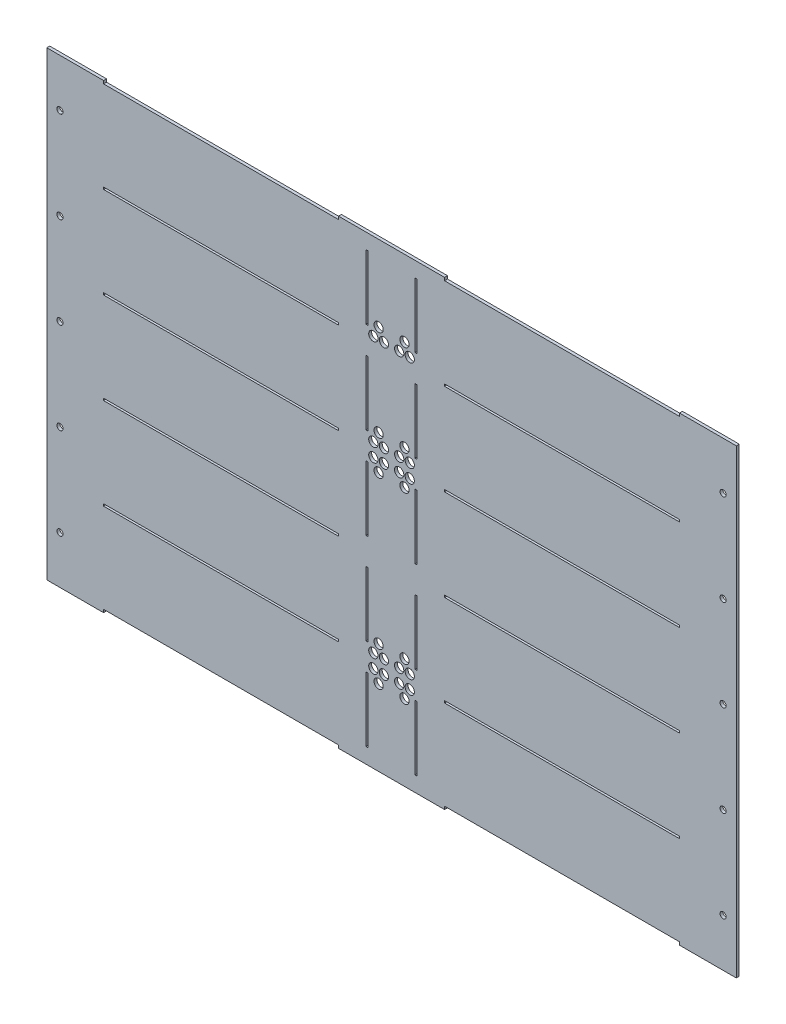
SolidWorks part; units mm, degrees
material "6061-T6 (SS)"
ref_plane "X-Y Datum" through (0, 0, 0) normal (0, 0, 1) x (1, 0, 0)
ref_plane "X-Z Datum" through (0, 0, 0) normal (0, 1, 0) x (1, 0, 0)
ref_plane "Y-Z Datum" through (0, 0, 0) normal (1, 0, 0) x (0, 0, -1)
sketch "Master Sketch" plane through (0, 0, 0) normal (0, 0, 1) x (1, 0, 0)
  line L5 (0, 249.174) -> (0, -249.174) construction
  line L6 (-344.2208, 249.174) -> (344.2208, 249.174)
  line L11 (-344.2208, 249.174) -> (-344.2208, -249.174)
  line L12 (-344.2208, -249.174) -> (344.2208, -249.174)
  line L17 (344.2208, 249.174) -> (344.2208, -249.174)
  line L34 (-344.2208, 249.174) -> (344.2208, -249.174) construction
  line L50 (-344.2208, -249.174) -> (344.2208, 249.174) construction
  line L51 (-25.4, 0) -> (25.4, 0) construction
  line L58 (25.4, 249.174) -> (25.4, -249.174) construction
  line L63 (-25.4, 249.174) -> (-25.4, -249.174) construction
  line L65 (27.686, 50.5714) -> (341.0458, 50.5714) construction
  line L66 (27.686, 245.999) -> (341.0458, 245.999) construction
  line L67 (27.686, 245.999) -> (27.686, 149.4282) construction
  line L68 (27.686, 149.4282) -> (341.0458, 149.4282) construction
  line L69 (341.0458, 245.999) -> (341.0458, 149.4282) construction
  line L70 (27.686, 245.999) -> (341.0458, 149.4282) construction
  line L71 (27.686, 149.4282) -> (341.0458, 245.999) construction
  line L72 (27.686, 147.1422) -> (27.686, 50.5714) construction
  line L73 (27.686, 147.1422) -> (341.0458, 147.1422) construction
  line L74 (341.0458, 147.1422) -> (341.0458, 50.5714) construction
  line L75 (27.686, 147.1422) -> (341.0458, 50.5714) construction
  line L76 (27.686, 50.5714) -> (341.0458, 147.1422) construction
  line L77 (27.686, -48.2854) -> (341.0458, -48.2854) construction
  line L78 (27.686, 48.2854) -> (27.686, -48.2854) construction
  line L79 (27.686, 48.2854) -> (341.0458, 48.2854) construction
  line L80 (341.0458, 48.2854) -> (341.0458, -48.2854) construction
  line L81 (27.686, 48.2854) -> (341.0458, -48.2854) construction
  line L82 (27.686, -48.2854) -> (341.0458, 48.2854) construction
  line L83 (27.686, -147.1422) -> (341.0458, -147.1422) construction
  line L84 (27.686, -50.5714) -> (27.686, -147.1422) construction
  line L85 (27.686, -50.5714) -> (341.0458, -50.5714) construction
  line L86 (341.0458, -50.5714) -> (341.0458, -147.1422) construction
  line L87 (27.686, -50.5714) -> (341.0458, -147.1422) construction
  line L88 (27.686, -147.1422) -> (341.0458, -50.5714) construction
  line L89 (27.686, -245.999) -> (341.0458, -245.999) construction
  line L90 (27.686, -149.4282) -> (27.686, -245.999) construction
  line L91 (27.686, -149.4282) -> (341.0458, -149.4282) construction
  line L92 (341.0458, -149.4282) -> (341.0458, -245.999) construction
  line L93 (27.686, -149.4282) -> (341.0458, -245.999) construction
  line L94 (27.686, -245.999) -> (341.0458, -149.4282) construction
  line L95 (0, -55) -> (0, 55) construction
  line L96 (-341.0458, -149.4282) -> (-341.0458, -245.999) construction
  line L97 (-27.686, -245.999) -> (-341.0458, -245.999) construction
  line L98 (-27.686, -149.4282) -> (-341.0458, -245.999) construction
  line L99 (-27.686, -245.999) -> (-341.0458, -149.4282) construction
  line L100 (-27.686, -149.4282) -> (-341.0458, -149.4282) construction
  line L101 (-27.686, -149.4282) -> (-27.686, -245.999) construction
  line L102 (-341.0458, -50.5714) -> (-341.0458, -147.1422) construction
  line L103 (-27.686, -50.5714) -> (-341.0458, -147.1422) construction
  line L104 (-27.686, -147.1422) -> (-341.0458, -50.5714) construction
  line L105 (-27.686, -147.1422) -> (-341.0458, -147.1422) construction
  line L106 (-27.686, -50.5714) -> (-27.686, -147.1422) construction
  line L107 (-27.686, -50.5714) -> (-341.0458, -50.5714) construction
  line L108 (-341.0458, 48.2854) -> (-341.0458, -48.2854) construction
  line L109 (-27.686, -48.2854) -> (-341.0458, -48.2854) construction
  line L110 (-27.686, -48.2854) -> (-341.0458, 48.2854) construction
  line L111 (-27.686, 48.2854) -> (-341.0458, -48.2854) construction
  line L112 (-27.686, 48.2854) -> (-341.0458, 48.2854) construction
  line L113 (-27.686, 48.2854) -> (-27.686, -48.2854) construction
  line L114 (-341.0458, 147.1422) -> (-341.0458, 50.5714) construction
  line L115 (-27.686, 50.5714) -> (-341.0458, 147.1422) construction
  line L116 (-27.686, 50.5714) -> (-341.0458, 50.5714) construction
  line L117 (-27.686, 147.1422) -> (-341.0458, 50.5714) construction
  line L118 (-27.686, 147.1422) -> (-27.686, 50.5714) construction
  line L119 (-27.686, 147.1422) -> (-341.0458, 147.1422) construction
  line L120 (-341.0458, 245.999) -> (-341.0458, 149.4282) construction
  line L121 (-27.686, 149.4282) -> (-341.0458, 149.4282) construction
  line L122 (-27.686, 149.4282) -> (-341.0458, 245.999) construction
  line L123 (-27.686, 245.999) -> (-27.686, 149.4282) construction
  line L124 (-27.686, 245.999) -> (-341.0458, 149.4282) construction
  line L125 (-27.686, 245.999) -> (-341.0458, 245.999) construction
  point P0 (0, 0)
  point P9 (0, 0)
  point P13 (0, 0)
  point P16 (25.4, 0)
  point P18 (-25.4, 0)
  point P19 (184.3659, 197.7136)
  dimension "D1" = 498.348
  dimension "D2" = 50.8
  dimension "D3" = 313.3598
  dimension "D4" = 96.5708
  dimension "D5" = 3.175
  dimension "D6" = 3.175
  dimension "D7" = 2.286
  dimension "D8" = 5
  dimension "D9" = 2.286
  dimension "D10" = 688.4416
extrude "Boss-Extrude1" add sketch "Master Sketch" along normal blind 3.175
sketch "Sketch1" plane through (0, 0, 3.175) normal (0, 0, 1) x (1, 0, 0)
  line L0 (344.2208, 249.174) -> (-344.2208, 249.174) construction
  line L1 (-344.2208, -249.174) -> (-372.7958, -249.174)
  line L2 (-344.2208, -249.174) -> (-344.2208, 249.174)
  line L3 (-344.2208, 249.174) -> (-372.7958, 249.174)
  line L4 (-372.7958, -249.174) -> (-372.7958, 249.174)
  line L5 (-358.5083, 249.174) -> (-358.5083, -249.174) construction
  line L6 (0, 361.953) -> (0, -361.953) construction
  line L7 (-520.6133, 0) -> (520.6133, 0) construction
  circle A0 centre (-358.5083, 0) radius 3 construction
  circle A1 centre (-358.5083, 98.806) radius 3 construction
  circle A2 centre (-358.5083, 197.612) radius 3 construction
  circle A3 centre (-358.5083, 0) radius 3 construction
  circle A4 centre (-358.5083, 98.806) radius 3 construction
  circle A5 centre (-358.5083, -98.806) radius 3 construction
  circle A6 centre (-358.5083, 0) radius 3 construction
  circle A7 centre (-358.5083, -98.806) radius 3 construction
  circle A8 centre (-358.5083, -197.612) radius 3 construction
  point P13 (0, 0)
  point P17 (0, 0)
  line M8 (-344.2208, 249.174) -> (-344.2208, -249.174)
  dimension "D2" = 6
  dimension "D1" = 28.575
  dimension "D4" = 98.806
  dimension "D5" = 98.806
  dimension "D6" = 3
  dimension "D3" = 3
extrude "Boss-Extrude2" add sketch "Sketch1" against normal blind 3.175 contours L4 L1 L3 A7 A4 A3 M8
hole_wizard "M6 Clearance Hole1" positions "Sketch2" profile "Sketch3" hole size "M6" standard "ANSI Metric" end condition through all
sketch "Sketch2" plane through (0, 0, 3.175) normal (0, 0, 1) x (1, 0, 0)
  point P0 (-358.5083, -197.612)
  point P3 (-358.5083, -98.806)
  point P6 (-358.5083, 0)
  point P9 (-358.5083, 98.806)
  point P12 (-358.5083, 197.612)
sketch "Sketch3" plane through (-358.5083, -197.612, 3.175) normal (1, 0, 0) x (0, -1, 0)
  line L0 (0, 0) -> (0, 3.175)
  line L1 (0, 3.175) -> (3.3, 3.175)
  line L2 (3.3, 3.175) -> (3.3, 0)
  line L5 (3.3, 0) -> (0, 0)
  line L11 (0, -6.35) -> (0, 107.95) construction
  dimension "Thru Hole Dia." = 6.6
  dimension "Thru Hole Depth" = 3.175
mirror "Mirror1" about plane through (0, 0, 0) normal (1, 0, 0) of "M6 Clearance Hole1", "Boss-Extrude2"
sketch "Sketch5" plane through (0, 0, 3.175) normal (0, 0, 1) x (1, 0, 0)
  line L0 (-184.3659, 197.7136) -> (184.3659, 197.7136) construction
  line L1 (-27.686, 149.4282) -> (-341.0458, 245.999) construction
  line L2 (27.686, 245.999) -> (27.686, 149.4282) construction
  line L3 (25.4, 197.7136) -> (27.686, 197.7136) construction
  line L4 (25.4, 249.174) -> (25.4, -249.174) construction
  line L5 (27.686, 197.7136) -> (26.543, 197.7136) construction
  line L6 (26.543, 197.7136) -> (26.543, 199.1948) construction
  line L7 (0, -1.7463) -> (0, 1.7463) construction
  line L8 (25.4, 232.6386) -> (27.686, 232.6386)
  line L9 (25.4, 232.6386) -> (25.4, 162.7886)
  line L10 (25.4, 162.7886) -> (27.686, 162.7886)
  line L11 (27.686, 232.6386) -> (27.686, 162.7886)
  line L12 (25.4, 232.6386) -> (27.686, 162.7886) construction
  line L13 (25.4, 162.7886) -> (27.686, 232.6386) construction
  line L14 (-25.4, 232.6386) -> (-27.686, 232.6386)
  line L15 (-25.4, 162.7886) -> (-27.686, 162.7886)
  line L16 (-25.4, 232.6386) -> (-25.4, 162.7886)
  line L17 (-27.686, 232.6386) -> (-27.686, 162.7886)
  dimension "D1" = 2.286
  dimension "D2" = 69.85
extrude "Cut-Extrude1" cut sketch "Sketch5" against normal through all
pattern_linear "LPattern1" count 5 spacing 98.8568 along (0, -1, 0) of "Cut-Extrude1"
sketch "Sketch6" plane through (0, 0, 3.175) normal (0, 0, 1) x (1, 0, 0)
  line L0 (-184.3659, 245.999) -> (-184.3659, 249.174) construction
  line L1 (-27.686, 245.999) -> (-341.0458, 245.999) construction
  line L2 (-344.2208, 249.174) -> (344.2208, 249.174) construction
  line L3 (0, -1.7463) -> (0, 1.7463) construction
  line L4 (-311.3659, 249.174) -> (-57.3659, 249.174)
  line L5 (-311.3659, 249.174) -> (-311.3659, 245.999)
  line L6 (-311.3659, 245.999) -> (-57.3659, 245.999)
  line L7 (-57.3659, 249.174) -> (-57.3659, 245.999)
  line L8 (-311.3659, 249.174) -> (-57.3659, 245.999) construction
  line L9 (-311.3659, 245.999) -> (-57.3659, 249.174) construction
  line L10 (57.3659, 249.174) -> (57.3659, 245.999)
  line L11 (311.3659, 245.999) -> (57.3659, 245.999)
  line L12 (311.3659, 249.174) -> (311.3659, 245.999)
  line L13 (311.3659, 249.174) -> (57.3659, 249.174)
  point P6 (-184.3659, 247.5865)
  dimension "D1" = 3.175
  dimension "D2" = 254
extrude "Cut-Extrude2" cut sketch "Sketch6" against normal through all
mirror "Mirror2" about plane through (0, 0, 0) normal (0, 1, 0) of "Cut-Extrude2"
sketch "Sketch7" plane through (0, 0, 3.175) normal (0, 0, 1) x (1, 0, 0)
  line L0 (-184.3659, 149.4282) -> (-184.3659, 147.1422) construction
  line L1 (-27.686, 149.4282) -> (-341.0458, 149.4282) construction
  line L2 (-27.686, 147.1422) -> (-341.0458, 147.1422) construction
  line L3 (0, -1.7463) -> (0, 1.7463) construction
  line L4 (-311.3659, 149.4282) -> (-57.3659, 149.4282)
  line L5 (-311.3659, 149.4282) -> (-311.3659, 147.1422)
  line L6 (-311.3659, 147.1422) -> (-57.3659, 147.1422)
  line L7 (-57.3659, 149.4282) -> (-57.3659, 147.1422)
  line L8 (-311.3659, 149.4282) -> (-57.3659, 147.1422) construction
  line L9 (-311.3659, 147.1422) -> (-57.3659, 149.4282) construction
  line L10 (57.3659, 149.4282) -> (57.3659, 147.1422)
  line L11 (311.3659, 149.4282) -> (311.3659, 147.1422)
  line L12 (311.3659, 147.1422) -> (57.3659, 147.1422)
  line L13 (311.3659, 149.4282) -> (57.3659, 149.4282)
  point P6 (-184.3659, 148.2852)
  dimension "D1" = 2.286
  dimension "D2" = 254
extrude "Cut-Extrude3" cut sketch "Sketch7" against normal through all
pattern_linear "LPattern2" count 4 spacing 98.8568 along (0, -1, 0) of "Cut-Extrude3"
sketch "Sketch8" plane through (0, 0, 0) normal (0, 0, -1) x (-1, 0, 0)
  line L0 (8.255, -155.5919) -> (19.685, -155.5919)
  line L1 (13.97, -167.0219) -> (13.97, -155.5919)
  line L2 (25.4, -232.6386) -> (25.4, -162.7886) construction
  line L3 (25.4, -162.7886) -> (27.686, -162.7886) construction
  line L4 (-57.3659, -148.2852) -> (57.3659, -148.2852) construction
  line L5 (-57.3659, -147.1422) -> (-57.3659, -149.4282) construction
  line L6 (57.3659, -149.4282) -> (57.3659, -147.1422) construction
  circle A0 centre (8.255, -155.5919) radius 5
  circle A2 centre (19.685, -155.5919) radius 5
  circle A3 centre (13.97, -167.0219) radius 5
  circle A4 centre (19.685, -140.9785) radius 5
  circle A5 centre (13.97, -129.5485) radius 5
  circle A6 centre (8.255, -140.9785) radius 5
  dimension "D1" = 10
  dimension "D2" = 11.43
  dimension "D3" = 11.43
  dimension "D4" = 11.43
  dimension "D5" = 4.2333
extrude "Cut-Extrude4" cut sketch "Sketch8" against normal through all
mirror "Mirror3" about plane through (0, 0, 0) normal (1, 0, 0) of "Cut-Extrude4"
pattern_linear "LPattern3" count 2 spacing 197.7136 along (0, 1, 0) of "Cut-Extrude4", "Mirror3"
sketch "Sketch9" plane through (0, 0, 0) normal (0, 0, -1) x (-1, 0, 0)
  line L0 (13.97, -167.0219) -> (13.97, -155.5919) construction
  line L1 (8.255, -155.5919) -> (19.685, -155.5919) construction
  line L2 (13.97, -167.0219) -> (13.97, -155.5919)
  line L3 (8.255, -155.5919) -> (19.685, -155.5919)
  circle A1 centre (8.255, -140.9785) radius 5
  circle A2 centre (8.255, -140.9785) radius 5
  circle A3 centre (13.97, -129.5485) radius 5
  circle A4 centre (13.97, -129.5485) radius 5
  circle A5 centre (19.685, -140.9785) radius 5
  circle A6 centre (19.685, -140.9785) radius 5
  circle A7 centre (13.97, -167.0219) radius 5
  circle A8 centre (13.97, -167.0219) radius 5
  circle A9 centre (19.685, -155.5919) radius 5
  circle A10 centre (19.685, -155.5919) radius 5
  circle A11 centre (8.255, -155.5919) radius 5
  circle A12 centre (8.255, -155.5919) radius 5
  dimension "D1" = 0
  dimension "D2" = 0
  dimension "D3" = 0
  dimension "D4" = 0
  dimension "D5" = 0
  dimension "D6" = 0
extrude "Cut-Extrude5" cut sketch "Sketch9" against normal through all contours A2 | A4 | A6
mirror "Mirror4" about plane through (0, 0, 0) normal (1, 0, 0) of "Cut-Extrude5"
pattern_linear "LPattern4" count 4 spacing 98.8568 along (0, 1, 0) skipping (1, 0) of "Mirror4", "Cut-Extrude5"
